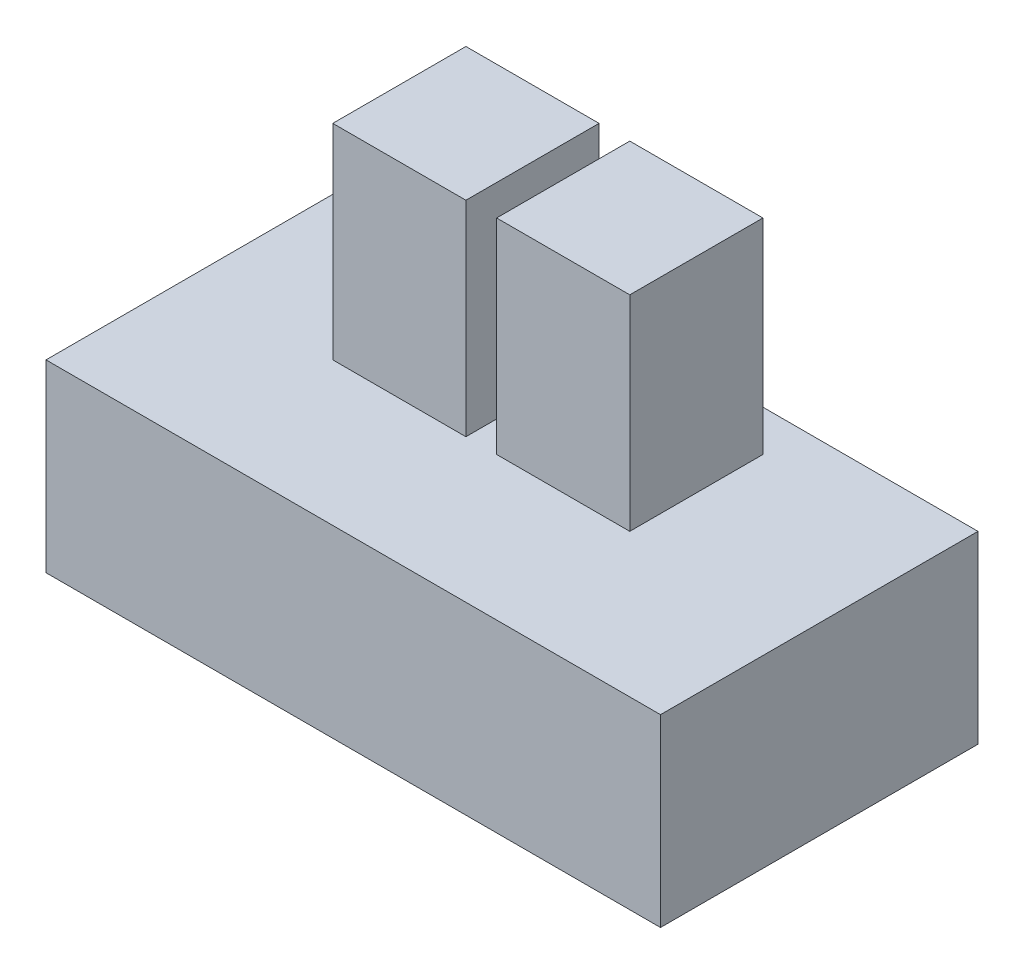
SolidWorks part; units mm, degrees
ref_plane "Piano frontale" through (0, 0, 0) normal (0, 0, 1) x (1, 0, 0)
ref_plane "Piano superiore" through (0, 0, 0) normal (0, 1, 0) x (1, 0, 0)
ref_plane "Piano destro" through (0, 0, 0) normal (1, 0, 0) x (0, 0, -1)
sketch "Schizzo1" plane through (0, 0, 0) normal (0, 1, 0) x (1, 0, 0)
  line L1 (-40.807, 8.8852) -> (19.193, 8.8852)
  line L2 (-40.807, 8.8852) -> (-40.807, -22.1148)
  line L3 (-40.807, -22.1148) -> (19.193, -22.1148)
  line L4 (19.193, 8.8852) -> (19.193, -22.1148)
  dimension "D1" = 31
  dimension "D2" = 60
extrude "Estrusione-Estrusione1" add sketch "Schizzo1" along normal blind 18
sketch "Schizzo2" plane through (0, 18, 0) normal (0, 1, 0) x (1, 0, 0)
  line L0 (-40.807, 8.8852) -> (-40.807, -22.1148) construction
  line L1 (-26.807, 4.8852) -> (-13.807, 4.8852)
  line L2 (-26.807, 4.8852) -> (-26.807, -8.1148)
  line L3 (-26.807, -8.1148) -> (-13.807, -8.1148)
  line L4 (-13.807, 4.8852) -> (-13.807, -8.1148)
  line L5 (-10.807, 4.8852) -> (2.193, 4.8852)
  line L6 (-10.807, 4.8852) -> (-10.807, -8.1148)
  line L7 (-10.807, -8.1148) -> (2.193, -8.1148)
  line L8 (2.193, 4.8852) -> (2.193, -8.1148)
  line L9 (19.193, 8.8852) -> (-40.807, 8.8852) construction
  dimension "D1" = 13
  dimension "D2" = 13
  dimension "D3" = 14
  dimension "D4" = 3
  dimension "D5" = 4
extrude "Estrusione-Estrusione2" add sketch "Schizzo2" along normal blind 20
sketch "Schizzo3" plane through (-40.807, 0, 0) normal (-1, 0, 0) x (0, 0, 1)
  line L0 (-8.8852, 0) -> (22.1148, 0) construction
  line L1 (-4.3852, 9) -> (-1.3852, 9)
  line L2 (-4.3852, 9) -> (-4.3852, 6)
  line L3 (-4.3852, 6) -> (-1.3852, 6)
  line L4 (-1.3852, 9) -> (-1.3852, 6)
  line L5 (1.1148, 9) -> (4.1148, 9)
  line L6 (1.1148, 9) -> (1.1148, 6)
  line L7 (1.1148, 6) -> (4.1148, 6)
  line L8 (4.1148, 9) -> (4.1148, 6)
  line L9 (9.1148, 9) -> (12.1148, 9)
  line L10 (9.1148, 9) -> (9.1148, 6)
  line L11 (9.1148, 6) -> (12.1148, 6)
  line L12 (12.1148, 9) -> (12.1148, 6)
  line L13 (14.6148, 9) -> (17.6148, 9)
  line L14 (14.6148, 9) -> (14.6148, 6)
  line L15 (14.6148, 6) -> (17.6148, 6)
  line L16 (17.6148, 9) -> (17.6148, 6)
  line L17 (6.6148, 18) -> (6.6148, 0) construction
  line L18 (-8.8852, 18) -> (22.1148, 18) construction
  line L19 (4.1148, 6) -> (6.6148, 6) construction
  line L20 (6.6148, 6) -> (9.1148, 6) construction
  line L21 (-1.3852, 6) -> (1.1148, 6) construction
  line L22 (12.1148, 6) -> (14.6148, 6) construction
  dimension "D1" = 3
  dimension "D2" = 6
  dimension "D3" = 2.5
  dimension "D4" = 2.5
extrude "Taglio-Estrusione1" cut sketch "Schizzo3" against normal blind 5
